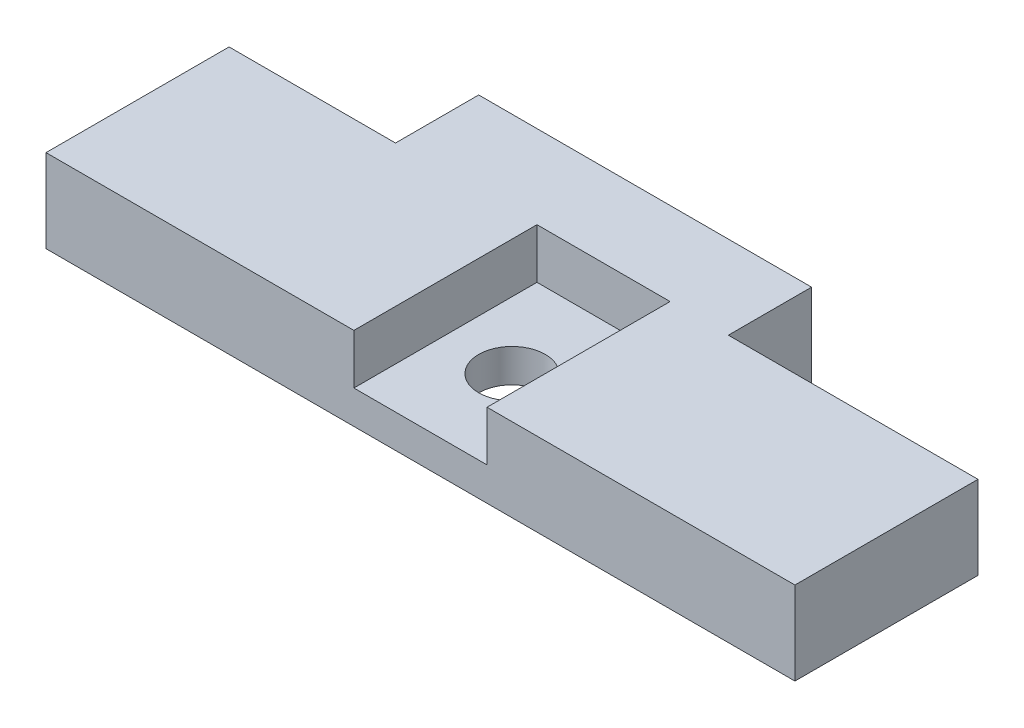
SolidWorks part; units mm, degrees
ref_plane "Plan de face" through (0, 0, 0) normal (0, 0, 1) x (1, 0, 0)
ref_plane "Plan de dessus" through (0, 0, 0) normal (0, 1, 0) x (1, 0, 0)
ref_plane "Plan de droite" through (0, 0, 0) normal (1, 0, 0) x (0, 0, -1)
sketch "Esquisse1" plane through (0, 0, 0) normal (0, 1, 0) x (1, 0, 0)
  line L0 (7.5, 8) -> (7.5, 3)
  line L1 (-12.5, 8) -> (7.5, 8)
  line L2 (-22.5, 3) -> (-22.5, -8)
  line L3 (-22.5, -8) -> (22.5, -8)
  line L4 (22.5, 3) -> (22.5, -8)
  line L5 (-22.5, 8) -> (22.5, -8) construction
  line L6 (-22.5, -8) -> (22.5, 8) construction
  line L7 (-12.5, 8) -> (-12.5, 3)
  line L8 (-12.5, 3) -> (-22.5, 3)
  line L9 (7.5, 3) -> (22.5, 3)
  point P0 (0, 0)
  dimension "D1" = 45
  dimension "D2" = 16
  dimension "D3" = 15
  dimension "D4" = 10
  dimension "D5" = 5
  dimension "D6" = 5
extrude "Boss.-Extru.1" add sketch "Esquisse1" along normal blind 5
sketch "Esquisse2" plane through (0, 5, 0) normal (0, 1, 0) x (1, 0, 0)
  line L0 (4, -8) -> (-4, -8)
  line L1 (-22.5, -8) -> (22.5, -8) construction
  line L2 (4, -8) -> (4, 3)
  line L3 (-4, -8) -> (-4, 3)
  line L4 (4, 3) -> (-4, 3)
  dimension "D1" = 11
  dimension "D2" = 8
extrude "Enlèv. mat.-Extru.1" cut sketch "Esquisse2" against normal blind 3
sketch "Esquisse3" plane through (0, 2, 0) normal (0, 1, 0) x (1, 0, 0)
  line L0 (-4, -8) -> (4, -8) construction
  circle A0 centre (0, -2.5) radius 2
  dimension "D1" = 4
  dimension "D2" = 5.5
extrude "Enlèv. mat.-Extru.3" cut sketch "Esquisse3" against normal through all
